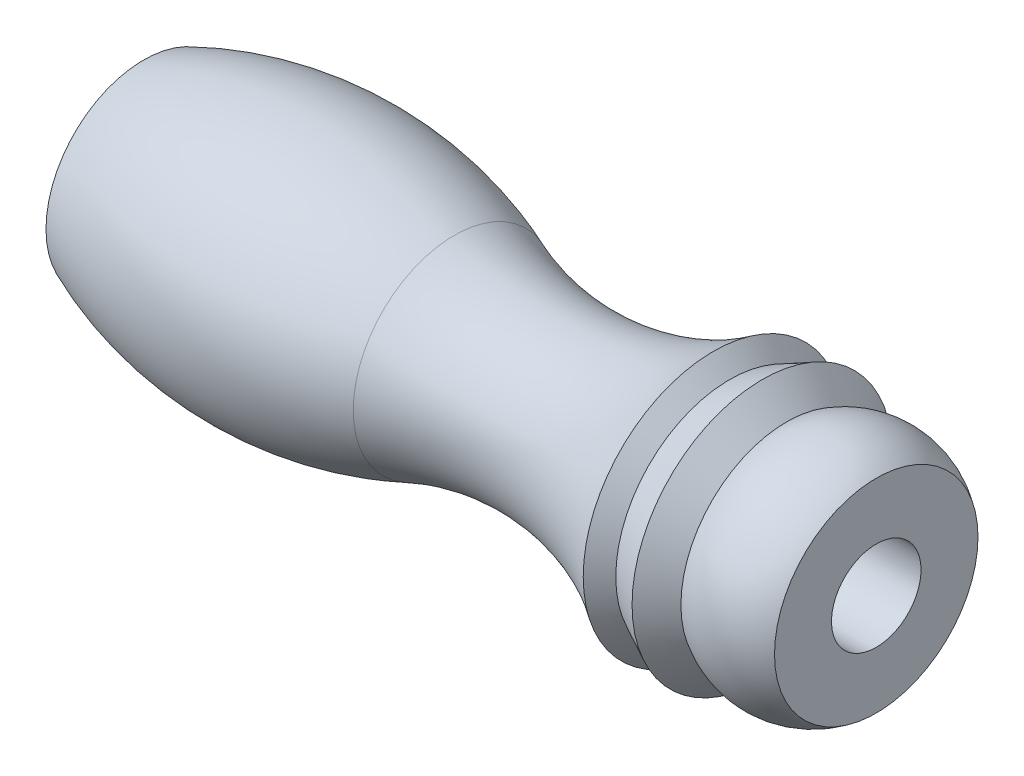
SolidWorks part; units mm, degrees
material "轻木"
ref_plane "前视基准面" through (0, 0, 0) normal (0, 0, 1) x (1, 0, 0)
ref_plane "上视基准面" through (0, 0, 0) normal (0, 1, 0) x (1, 0, 0)
ref_plane "右视基准面" through (0, 0, 0) normal (1, 0, 0) x (0, 0, -1)
sketch "草图1" plane through (0, 0, 0) normal (0, 0, 1) x (1, 0, 0)
  line L0 (0, 0) -> (90, 0) construction
  line L1 (55, 0) -> (-55, 0) construction
  line L2 (0, 0) -> (0, 12)
  line L4 (70, 16) -> (72, 14)
  line L5 (72, 14) -> (76, 16)
  line L6 (76, 16) -> (79, 13)
  line L7 (90, 12.5) -> (90, 0)
  line L8 (0, 0) -> (90, 0)
  arc A0 (38.1663, 12.4235) -> (0, 12) centre (19.5959, -34) ccw
  arc A1 (38.1663, 12.4235) -> (70, 16) centre (50.7499, 43.8807) ccw
  arc A2 (79, 13) -> (90, 12.5) centre (84.1209, 4.4107) cw
  dimension "D2" = 50
  dimension "D3" = 20
  dimension "D8" = 10
  dimension "D11" = 32
  dimension "D12" = 20
  dimension "D16" = 33.8807
  dimension "D1" = 90
  dimension "D4" = 32
  dimension "D5" = 28
  dimension "D6" = 32
  dimension "D7" = 3
  dimension "D9" = 25
  dimension "D10" = 24
  dimension "D13" = 2
  dimension "D14" = 4
  dimension "D15" = 26
revolve "旋转1" add sketch "草图1" angle 360 about L0
sketch "草图2" plane through (90, 0, 0) normal (1, 0, 0) x (0, 0, -1)
  circle A0 centre (0, 0) radius 5.5
  dimension "D1" = 11
extrude "切除-拉伸1" cut sketch "草图2" against normal through all
